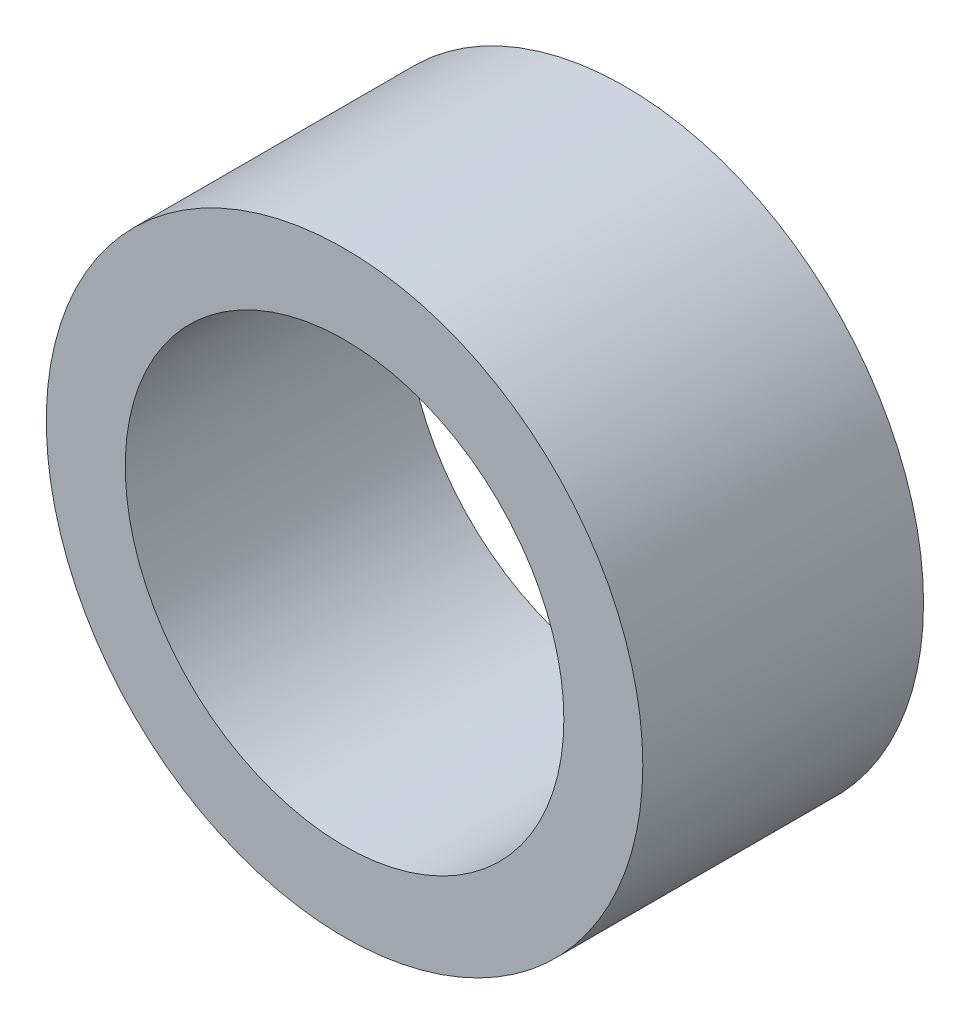
SolidWorks part; units mm, degrees
ref_plane "Спереди" through (0, 0, 0) normal (0, 0, 1) x (1, 0, 0)
ref_plane "Сверху" through (0, 0, 0) normal (0, 1, 0) x (1, 0, 0)
ref_plane "Справа" through (0, 0, 0) normal (1, 0, 0) x (0, 0, -1)
sketch "Эскиз1" plane through (0, 0, 0) normal (0, 0, 1) x (1, 0, 0)
  circle A0 centre (0, 0) radius 17
  circle A1 centre (0, 0) radius 12.5
extrude "Needle_outer_hub" add sketch "Эскиз1" along normal blind 16 from offset 55.5
